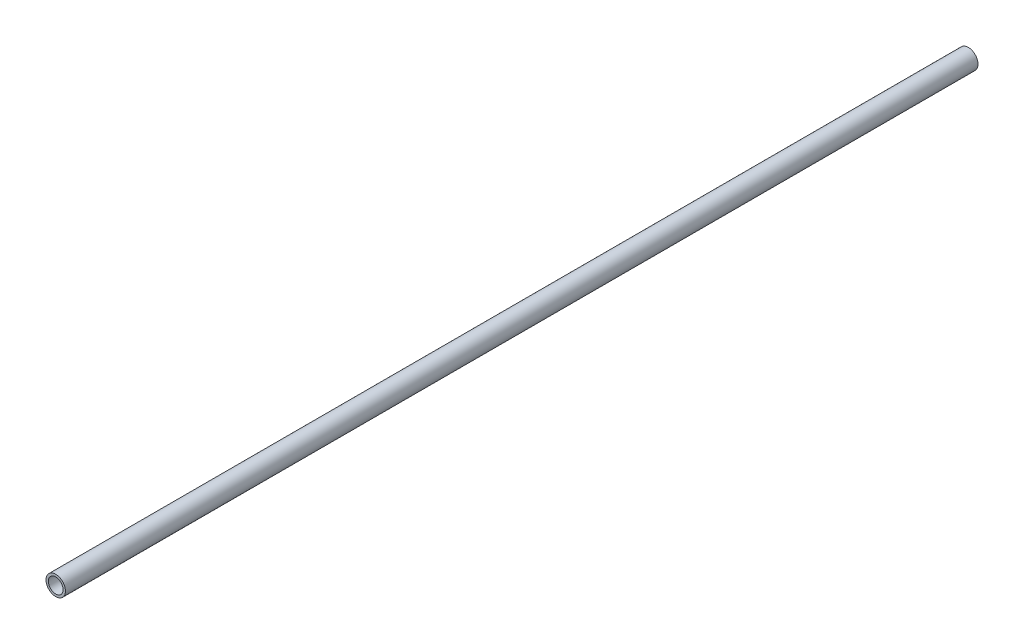
SolidWorks part; units mm, degrees
material "Plain Carbon Steel"
ref_plane "Front Plane" through (0, 0, 0) normal (0, 0, 1) x (1, 0, 0)
ref_plane "Top Plane" through (0, 0, 0) normal (0, 1, 0) x (1, 0, 0)
ref_plane "Right Plane" through (0, 0, 0) normal (1, 0, 0) x (0, 0, -1)
sketch "Sketch1" plane through (0, 0, 0) normal (0, 0, 1) x (1, 0, 0)
  circle A0 centre (0, 0) radius 12.7
  circle A1 centre (0, 0) radius 16.7005
extrude "Boss-Extrude1" add sketch "Sketch1" along normal blind 1568.196
